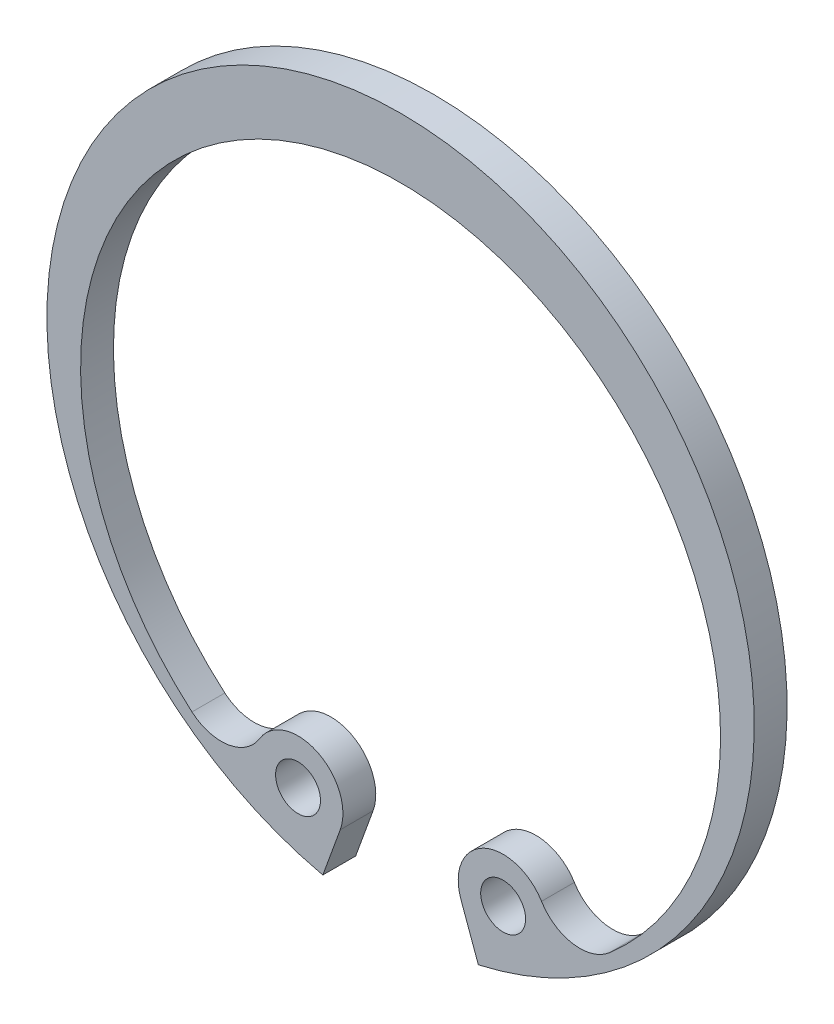
SolidWorks part; units mm, degrees
material "Plain Carbon Steel"
ref_plane "Front Plane" through (0, 0, 0) normal (0, 0, 1) x (1, 0, 0)
ref_plane "Top Plane" through (0, 0, 0) normal (0, 1, 0) x (1, 0, 0)
ref_plane "Right Plane" through (0, 0, 0) normal (1, 0, 0) x (0, 0, -1)
ref_plane "Plane1" through (0, 0, 0.975) normal (0, 0, -1) x (-1, 0, 0)
sketch "Sketch1" plane through (0, 0, 0.975) normal (0, 0, -1) x (-1, 0, 0)
  line L0 (1.7918, -8.8213) -> (2.3092, -10.2429)
  line L1 (-2.3092, -10.2429) -> (-1.7918, -8.8213)
  arc A0 (6.1928, -7.9915) -> (4.1842, -7.6729) centre (5.3236, -6.9804) cw
  arc A1 (4.1842, -7.6729) -> (1.7918, -8.8213) centre (3.0447, -8.3653) ccw
  arc A2 (2.3092, -10.2429) -> (-2.3092, -10.2429) centre (0, 0) ccw
  arc A3 (-1.7918, -8.8213) -> (-4.1842, -7.6729) centre (-3.0447, -8.3653) ccw
  arc A4 (-4.1842, -7.6729) -> (-6.1928, -7.9915) centre (-5.3236, -6.9804) cw
  arc A5 (-6.1928, -7.9915) -> (6.1928, -7.9915) centre (0, -0.7874) cw
  circle A6 centre (-3.0447, -8.3653) radius 0.6667
  circle A7 centre (3.0447, -8.3653) radius 0.6667
extrude "Boss-Extrude1" add sketch "Sketch1" against normal blind 0.975
